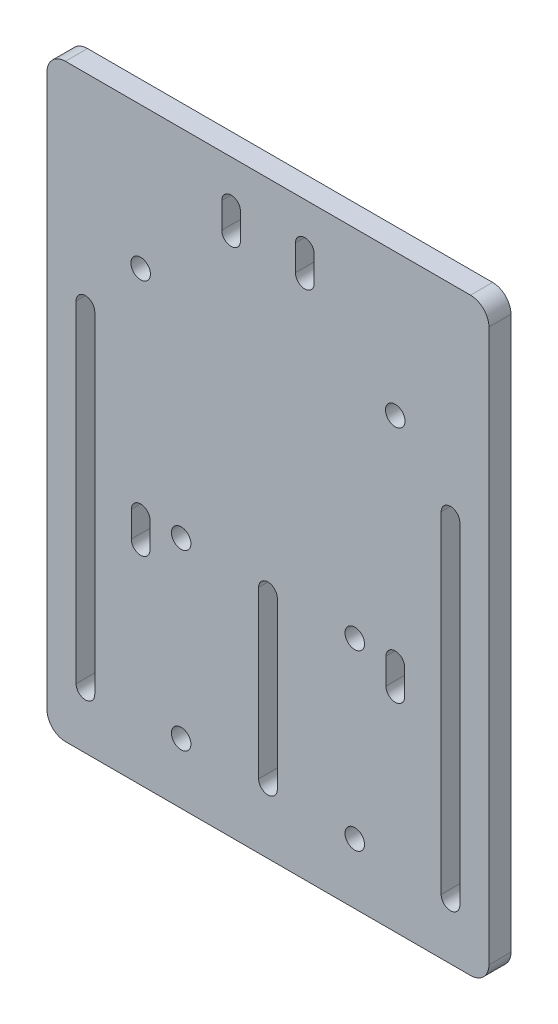
SolidWorks part; units mm, degrees
ref_plane "Front Plane" through (0, 0, 0) normal (0, 0, 1) x (1, 0, 0)
ref_plane "Top Plane" through (0, 0, 0) normal (0, 1, 0) x (1, 0, 0)
ref_plane "Right Plane" through (0, 0, 0) normal (1, 0, 0) x (0, 0, -1)
sketch "Sketch2" plane through (0, 0, 0) normal (0, 0, 1) x (1, 0, 0)
  line L1 (-55, -80) -> (55, -80)
  line L2 (-60, -75) -> (-60, 75)
  line L3 (-55, 80) -> (55, 80)
  line L4 (60, -75) -> (60, 75)
  line L5 (-60, -80) -> (60, 80) construction
  line L6 (-60, 80) -> (60, -80) construction
  arc A0 (55, -80) -> (60, -75) centre (55, -75) ccw
  arc A1 (-55, -80) -> (-60, -75) centre (-55, -75) cw
  arc A2 (55, 80) -> (60, 75) centre (55, 75) cw
  arc A3 (-60, 75) -> (-55, 80) centre (-55, 75) cw
  point P0 (0, 0)
  dimension "D3" = 5
  dimension "D1" = 120
  dimension "D2" = 160
extrude "Boss-Extrude1" add sketch "Sketch2" along normal blind 6
sketch "Sketch3" plane through (0, 0, 6) normal (0, 0, 1) x (1, 0, 0)
  line L0 (0, -17.5) -> (0, -62.5) construction
  line L1 (2.54, -17.5) -> (2.54, -62.5)
  line L2 (-2.54, -17.5) -> (-2.54, -62.5)
  line L3 (-55, -80) -> (55, -80) construction
  arc A0 (2.54, -17.5) -> (-2.54, -17.5) centre (0, -17.5) ccw
  arc A1 (-2.54, -62.5) -> (2.54, -62.5) centre (0, -62.5) ccw
  point P3 (0, -40)
  point P10 (0, 0)
  dimension "D1" = 2.54
  dimension "D2" = 45
  dimension "D3" = 40
extrude "Cut-Extrude1" cut sketch "Sketch3" against normal blind 6
hole_wizard "M5 Clearance Hole1" positions "Sketch4" profile "Sketch5" hole size "M5" standard "ANSI Metric" end condition through all
sketch "Sketch4" plane through (0, 0, 6) normal (0, 0, 1) x (1, 0, 0)
  point P0 (-23.57, -63.57)
  point P2 (-23.57, -16.43)
  point P4 (23.57, -16.43)
  point P6 (23.57, -63.57)
  dimension "D1" = 23.57
  dimension "D2" = 23.57
  dimension "D3" = 23.57
  dimension "D4" = 47.14
sketch "Sketch5" plane through (-23.57, -63.57, 6) normal (1, 0, 0) x (0, -1, 0)
  line L0 (0, 0) -> (0, 6)
  line L1 (0, 6) -> (2.65, 6)
  line L2 (2.65, 6) -> (2.65, 0)
  line L5 (2.65, 0) -> (0, 0)
  line L11 (0, -6.35) -> (0, 107.95) construction
  dimension "Thru Hole Dia." = 5.3
  dimension "Thru Hole Depth" = 6
sketch "Sketch6" plane through (0, 0, 6) normal (0, 0, 1) x (1, 0, 0)
  line L0 (-34.57, -16.43) -> (-34.57, -23.43) construction
  line L1 (-32.03, -16.43) -> (-32.03, -23.43)
  line L2 (-37.11, -16.43) -> (-37.11, -23.43)
  arc A0 (-32.03, -16.43) -> (-37.11, -16.43) centre (-34.57, -16.43) ccw
  arc A1 (-37.11, -23.43) -> (-32.03, -23.43) centre (-34.57, -23.43) ccw
  point P2 (-34.57, -19.93)
  point P7 (0, 0)
  point P8 (0, 0)
  point P9 (0, 0)
  point P10 (0, 0)
  dimension "D1" = 2.54
  dimension "D2" = 7
  dimension "D3" = 11
extrude "Cut-Extrude2" cut sketch "Sketch6" against normal blind 22
hole_wizard "M5 Clearance Hole2" positions "Sketch7" profile "Sketch8" hole size "M5" standard "ANSI Metric" end condition through all
sketch "Sketch7" plane through (0, 0, 6) normal (0, 0, 1) x (1, 0, 0)
  point P0 (-34.57, 41.47)
  point P4 (0, 0)
  dimension "D1" = 61.4
sketch "Sketch8" plane through (-34.57, 41.47, 6) normal (1, 0, 0) x (0, -1, 0)
  line L0 (0, 0) -> (0, 6)
  line L1 (0, 6) -> (2.65, 6)
  line L2 (2.65, 6) -> (2.65, 0)
  line L5 (2.65, 0) -> (0, 0)
  line L11 (0, -6.35) -> (0, 107.95) construction
  dimension "Thru Hole Dia." = 5.3
  dimension "Thru Hole Depth" = 6
sketch "Sketch9" plane through (0, 0, 6) normal (0, 0, 1) x (1, 0, 0)
  line L0 (-49.57, 25.07) -> (-49.57, -64.93) construction
  line L1 (-47.03, 25.07) -> (-47.03, -64.93)
  line L2 (-52.11, 25.07) -> (-52.11, -64.93)
  arc A0 (-47.03, 25.07) -> (-52.11, 25.07) centre (-49.57, 25.07) ccw
  arc A1 (-52.11, -64.93) -> (-47.03, -64.93) centre (-49.57, -64.93) ccw
  point P2 (-49.57, -19.93)
  point P7 (0, 0)
  dimension "D2" = 2.54
  dimension "D1" = 15
  dimension "D3" = 90
extrude "Cut-Extrude3" cut sketch "Sketch9" against normal blind 6
sketch "Sketch10" plane through (0, 0, 6) normal (0, 0, 1) x (1, 0, 0)
  line L0 (0, 85.855) -> (0, -97.3195) construction
mirror "Mirror2" about plane through (0, 0, 0) normal (1, 0, 0) of "M5 Clearance Hole2", "Cut-Extrude3", "Cut-Extrude2"
sketch "Sketch11" plane through (0, 0, 6) normal (0, 0, 1) x (1, 0, 0)
  line L0 (-10, 68.5) -> (-10, 61.5) construction
  line L1 (-7.46, 68.5) -> (-7.46, 61.5)
  line L2 (-12.54, 68.5) -> (-12.54, 61.5)
  line L3 (10, 68.5) -> (10, 61.5) construction
  line L4 (12.54, 68.5) -> (12.54, 61.5)
  line L5 (7.46, 68.5) -> (7.46, 61.5)
  line L9 (55, 80) -> (-55, 80) construction
  arc A0 (-7.46, 68.5) -> (-12.54, 68.5) centre (-10, 68.5) ccw
  arc A1 (-12.54, 61.5) -> (-7.46, 61.5) centre (-10, 61.5) ccw
  arc A2 (12.54, 68.5) -> (7.46, 68.5) centre (10, 68.5) ccw
  arc A3 (7.46, 61.5) -> (12.54, 61.5) centre (10, 61.5) ccw
  point P2 (-10, 65)
  point P7 (10, 65)
  point P14 (0, 0)
  point P18 (-11.0974, 80)
  dimension "D1" = 2.54
  dimension "D4" = 10
  dimension "D2" = 7
  dimension "D3" = 20
  dimension "D5" = 15
extrude "Cut-Extrude4" cut sketch "Sketch11" against normal blind 6
